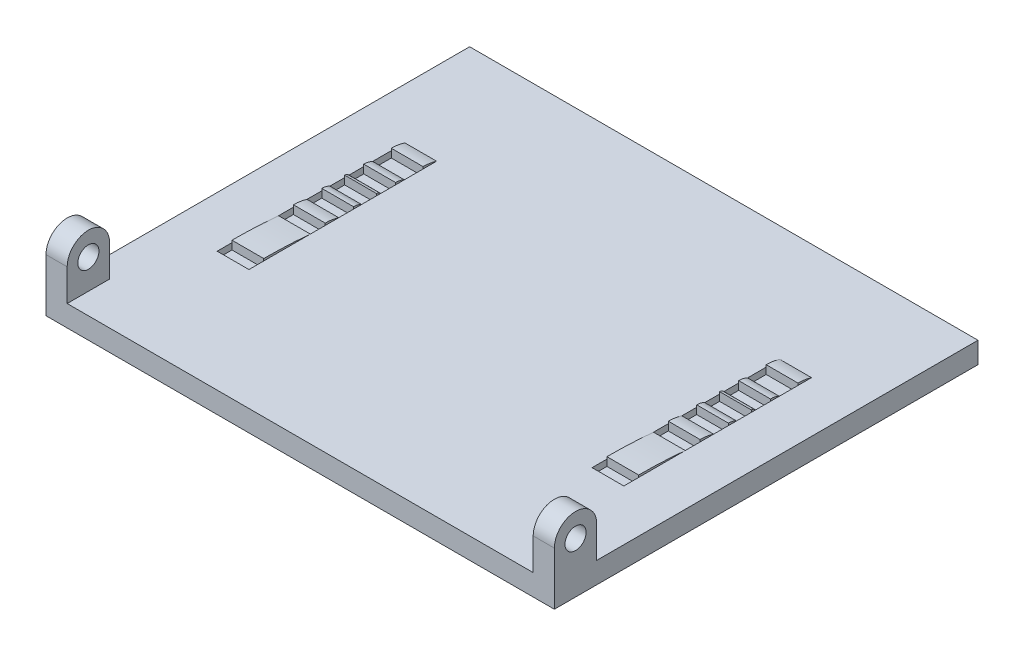
SolidWorks part; units mm, degrees
material "Oak"
ref_plane "Front Plane" through (0, 0, 0) normal (0, 0, 1) x (1, 0, 0)
ref_plane "Top Plane" through (0, 0, 0) normal (0, 1, 0) x (1, 0, 0)
ref_plane "Right Plane" through (0, 0, 0) normal (1, 0, 0) x (0, 0, -1)
sketch "Sketch1" plane through (0, 0, 0) normal (0, 1, 0) x (1, 0, 0)
  line L1 (-152.4, 127) -> (152.4, 127)
  line L2 (-152.4, 127) -> (-152.4, -127)
  line L3 (-152.4, -127) -> (152.4, -127)
  line L4 (152.4, 127) -> (152.4, -127)
  line L5 (-152.4, 127) -> (152.4, -127) construction
  line L6 (-152.4, -127) -> (152.4, 127) construction
  point P0 (0, 0)
  dimension "D1" = 304.8
  dimension "D2" = 254
extrude "Boss-Extrude1" add sketch "Sketch1" along normal blind 12.7
sketch "Sketch2" plane through (0, 12.7, 0) normal (0, 1, 0) x (1, 0, 0)
  line L1 (-152.4, -127) -> (-139.7, -127)
  line L2 (-152.4, -127) -> (-152.4, -101.6)
  line L3 (-152.4, -101.6) -> (-139.7, -101.6)
  line L4 (-139.7, -127) -> (-139.7, -101.6)
  dimension "D1" = 25.4
  dimension "D2" = 12.7
extrude "Boss-Extrude2" add sketch "Sketch2" along normal blind 19.05
sketch "Sketch4" plane through (-139.7, 0, 0) normal (1, 0, 0) x (0, 0, -1)
  line L0 (-127, 31.75) -> (-101.6, 31.75)
  arc A0 (-127, 31.75) -> (-101.6, 31.75) centre (-114.3, 31.75) cw
  dimension "D1" = 12.7
extrude "Boss-Extrude3" add sketch "Sketch4" against normal up to surface (12.7 mm away) up to face at (-152.4, 14.8167, 33.8667)
sketch "Sketch5" plane through (-139.7, 0, 0) normal (1, 0, 0) x (0, 0, -1)
  line L0 (-114.3, 12.7) -> (-114.3, 30.48) construction
  line L1 (-127, 12.7) -> (-101.6, 12.7) construction
  circle A0 centre (-114.3, 30.48) radius 6.35
  dimension "D2" = 12.7
  dimension "D1" = 17.78
extrude "Cut-Extrude1" cut sketch "Sketch5" against normal up to surface (12.7 mm away) up to face at (-152.4, 16.9333, 33.8667)
mirror "Mirror1" about plane through (0, 0, 0) normal (1, 0, 0) of "Cut-Extrude1", "Boss-Extrude3", "Boss-Extrude2"
sketch "Sketch6" plane through (0, 12.7, 0) normal (0, 1, 0) x (1, 0, 0)
  line L0 (-152.4, 127) -> (-152.4, -101.6) construction
  line L1 (-121.92, -45.974) -> (-102.87, -45.974)
  line L2 (-121.92, -45.974) -> (-121.92, -54.864)
  line L3 (-121.92, -54.864) -> (-102.87, -54.864)
  line L4 (-102.87, -45.974) -> (-102.87, -54.864)
  line L5 (-121.92, -45.974) -> (-102.87, -54.864) construction
  line L6 (-121.92, -54.864) -> (-102.87, -45.974) construction
  line L7 (-139.7, -101.6) -> (-152.4, -101.6) construction
  line L8 (-121.92, -9.144) -> (-121.92, -18.034)
  line L9 (-121.92, -9.144) -> (-102.87, -9.144)
  line L10 (-102.87, -9.144) -> (-102.87, -18.034)
  line L11 (-121.92, -18.034) -> (-102.87, -18.034)
  line L32 (-121.92, 21.59) -> (-102.87, 21.59)
  line L33 (-102.87, 175.006) -> (-102.87, 166.116) [skipped]
  line L34 (-121.92, 175.006) -> (-102.87, 175.006) [skipped]
  line L35 (-121.92, 166.116) -> (-102.87, 166.116) [skipped]
  line L36 (-121.92, 175.006) -> (-121.92, 166.116) [skipped]
  line L37 (-102.87, 138.176) -> (-102.87, 129.286) [skipped]
  line L38 (-121.92, 138.176) -> (-102.87, 138.176) [skipped]
  line L39 (-121.92, 138.176) -> (-121.92, 129.286) [skipped]
  line L40 (-121.92, 129.286) -> (-102.87, 129.286) [skipped]
  line L41 (-121.92, 27.686) -> (-121.92, 18.796) [skipped]
  line L42 (-121.92, 18.796) -> (-102.87, 18.796) [skipped]
  line L43 (-102.87, 27.686) -> (-102.87, 18.796) [skipped]
  line L44 (-121.92, 27.686) -> (-102.87, 27.686) [skipped]
  line L45 (-121.92, 64.516) -> (-121.92, 55.626) [skipped]
  line L46 (-121.92, 55.626) -> (-102.87, 55.626) [skipped]
  line L47 (-102.87, 64.516) -> (-102.87, 55.626) [skipped]
  line L48 (-121.92, 64.516) -> (-102.87, 64.516) [skipped]
  line L49 (-121.92, 101.346) -> (-121.92, 92.456) [skipped]
  line L50 (-121.92, 92.456) -> (-102.87, 92.456) [skipped]
  line L51 (-102.87, 101.346) -> (-102.87, 92.456) [skipped]
  line L52 (-121.92, 101.346) -> (-102.87, 101.346) [skipped]
  line L53 (-121.92, 7.874) -> (-102.87, 7.874)
  line L54 (-121.92, 7.874) -> (-121.92, -1.016)
  line L55 (-121.92, -1.016) -> (-102.87, -1.016)
  line L56 (-102.87, 7.874) -> (-102.87, -1.016)
  line L57 (-121.92, 21.59) -> (-121.92, 12.7)
  line L58 (-121.92, 12.7) -> (-102.87, 12.7)
  line L59 (-102.87, 21.59) -> (-102.87, 12.7)
  line L61 (-121.92, 33.02) -> (-102.87, 33.02)
  line L62 (-121.92, 33.02) -> (-121.92, 24.13)
  line L63 (-121.92, 24.13) -> (-102.87, 24.13)
  line L64 (-102.87, 33.02) -> (-102.87, 24.13)
  line L65 (-121.92, 49.53) -> (-102.87, 49.53)
  line L66 (-121.92, 49.53) -> (-121.92, 38.354)
  line L67 (-121.92, 38.354) -> (-102.87, 38.354)
  line L68 (-102.87, 49.53) -> (-102.87, 38.354)
  point P0 (-112.395, -50.419)
  point P29 (-112.395, 38.354)
  dimension "D1" = 19.05
  dimension "D2" = 8.89
  dimension "D3" = 30.48
  dimension "D4" = 46.736
  dimension "D6" = 27.94
  dimension "D7" = 8.128
  dimension "D8" = 4.826
  dimension "D9" = 2.54
  dimension "D10" = 5.334
  dimension "D11" = 11.176
  dimension "D5" = 7
extrude "Cut-Extrude2" cut sketch "Sketch6" against normal blind 3.81 contours L4 L1 L2 L3
sketch "Sketch7" plane through (-102.87, 0, 0) normal (-1, 0, 0) x (0, 0, 1)
  line L0 (45.974, 12.7) -> (45.974, 13.97)
  line L1 (45.974, 12.7) -> (18.034, 12.7)
  line L2 (9.144, 12.7) -> (9.144, 13.97)
  line L3 (9.144, 12.7) -> (1.016, 12.7)
  line L4 (-7.874, 12.7) -> (-12.7, 12.7)
  line L5 (-7.874, 12.7) -> (1.016, 12.7) construction
  line L6 (-7.874, 12.7) -> (-7.874, 13.97)
  line L7 (-21.59, 12.7) -> (-24.13, 12.7)
  line L8 (-21.59, 12.7) -> (-21.59, 13.97)
  line L9 (-33.02, 12.7) -> (-38.354, 12.7)
  line L10 (-33.02, 12.7) -> (-33.02, 13.97)
  line L11 (-33.02, 12.7) -> (-24.13, 12.7) construction
  line L12 (-49.53, 12.7) -> (-57.658, 12.7)
  line L13 (-49.53, 12.7) -> (-38.354, 12.7) construction
  line L14 (-49.53, 12.7) -> (-49.53, 13.97)
  arc A0 (45.974, 13.97) -> (18.034, 12.7) centre (45.974, -294.005) ccw
  arc A1 (9.144, 13.97) -> (1.016, 12.7) centre (9.144, -12.6746) ccw
  arc A2 (-7.874, 13.97) -> (-12.7, 12.7) centre (-7.874, 4.1656) ccw
  arc A3 (-21.59, 13.97) -> (-24.13, 12.7) centre (-21.59, 10.795) ccw
  arc A4 (-33.02, 13.97) -> (-38.354, 12.7) centre (-33.02, 2.1336) ccw
  arc A5 (-49.53, 13.97) -> (-57.658, 12.7) centre (-49.53, -12.6746) ccw
  dimension "D1" = 1.27
  dimension "D2" = 27.94
  dimension "D3" = 1.27
  dimension "D4" = 1.27
  dimension "D5" = 1.27
  dimension "D6" = 1.27
  dimension "D7" = 1.27
  dimension "D8" = 8.128
extrude "Boss-Extrude4" add sketch "Sketch7" along normal up to surface (19.05 mm away) up to face at (-121.92, 10.795, 13.589)
mirror "Mirror2" about plane through (0, 0, 0) normal (1, 0, 0) of "Boss-Extrude4", "Cut-Extrude2"
